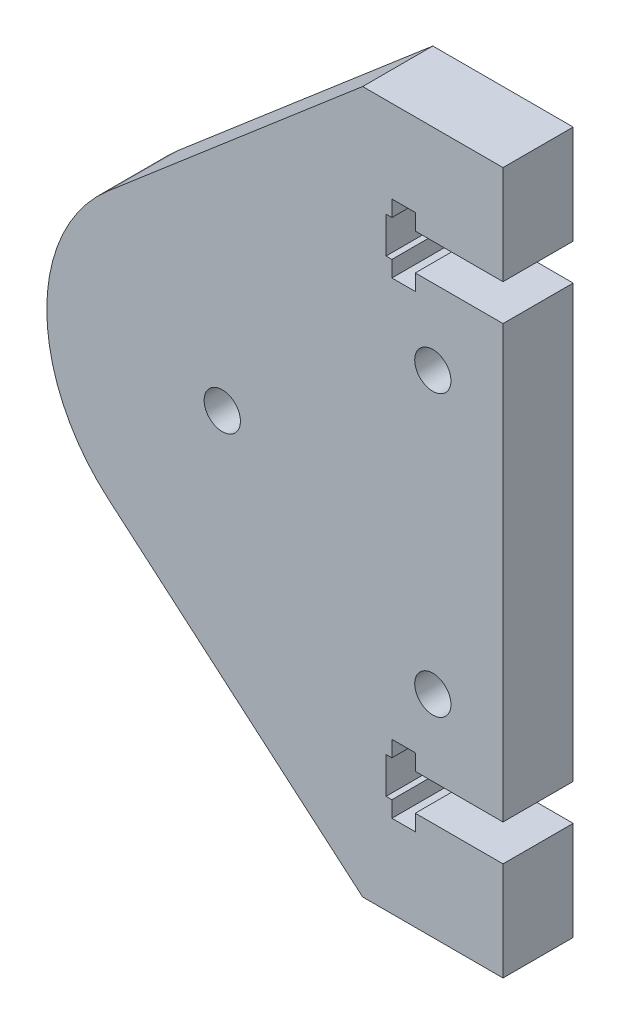
SolidWorks part; units mm, degrees
ref_plane "Płaszczyzna przednia" through (0, 0, 0) normal (0, 0, 1) x (1, 0, 0)
ref_plane "Płaszczyzna górna" through (0, 0, 0) normal (0, 1, 0) x (1, 0, 0)
ref_plane "Płaszczyzna prawa" through (0, 0, 0) normal (1, 0, 0) x (0, 0, -1)
sketch "Szkic1" plane through (0, 0, 0) normal (0, 0, 1) x (1, 0, 0)
  line L2 (-455.0646, -113.9558) -> (-476.8138, -95.3555)
  line L4 (-455.0646, -113.9558) -> (-443.0646, -113.9558)
  line L6 (-455.0646, -53.9558) -> (-476.8138, -72.5561)
  line L7 (-443.0646, -53.9558) -> (-455.0646, -53.9558)
  line L10 (-443.0646, -53.9558) -> (-443.0646, -113.9558)
  arc A0 (-476.8138, -72.5561) -> (-476.8138, -95.3555) centre (-467.0646, -83.9558) ccw
  dimension "D6" = 15
extrude "Dodanie-wyciągnięcie1" add sketch "Szkic1" along normal blind 6
sketch "Szkic2" plane through (0, 0, 6) normal (0, 0, 1) x (1, 0, 0)
  circle A0 centre (-467.0646, -83.9558) radius 1.55
  arc A1 (-476.8138, -72.5561) -> (-476.8138, -95.3555) centre (-467.0646, -83.9558) ccw construction
  dimension "D1" = 0
  dimension "D2" = 3.1
extrude "Wytnij-wyciągnięcie1" cut sketch "Szkic2" against normal blind 6
sketch "Szkic3" plane through (0, 0, 0) normal (0, 0, -1) x (-1, 0, 0)
  line L0 (443.0646, -113.9558) -> (443.0646, -53.9558) construction
  line L1 (443.0646, -105.5058) -> (450.5646, -105.5058)
  line L2 (443.0646, -105.5058) -> (443.0646, -102.4058)
  line L3 (443.0646, -102.4058) -> (450.5646, -102.4058)
  line L4 (453.0646, -105.5058) -> (453.0646, -102.4058)
  line L5 (452.5646, -105.5058) -> (453.0646, -105.5058)
  line L6 (452.5646, -106.8808) -> (450.5646, -106.8808)
  line L7 (452.5646, -106.8808) -> (452.5646, -105.5058)
  line L8 (452.5646, -101.0308) -> (450.5646, -101.0308)
  line L9 (450.5646, -106.8808) -> (450.5646, -105.5058)
  line L10 (450.5646, -102.4058) -> (450.5646, -101.0308)
  line L11 (452.5646, -102.4058) -> (453.0646, -102.4058)
  line L12 (452.5646, -102.4058) -> (452.5646, -101.0308)
  line L13 (455.0646, -113.9558) -> (443.0646, -113.9558) construction
  point P14 (443.0646, -103.9558)
  dimension "D1" = 10
  dimension "D2" = 0.5
  dimension "D3" = 2
  dimension "D4" = 3.1
  dimension "D5" = 1.375
  dimension "D6" = 5.85
  dimension "D7" = 10
extrude "Wytnij-wyciągnięcie2" cut sketch "Szkic3" against normal blind 6
pattern_linear "Szyk liniowy1" count 2 spacing 40 along (0, 1, 0) of "Wytnij-wyciągnięcie2"
sketch "Szkic4" plane through (0, 0, 0) normal (0, 0, -1) x (-1, 0, 0)
  circle A2 centre (449.0646, -95.9368) radius 1.55
  circle A3 centre (449.0646, -71.9708) radius 1.55
extrude "Wytnij-wyciągnięcie3" cut sketch "Szkic4" against normal blind 6
equation "\"tolerancja_wpusy\"=0.2"
equation "\"dlugosc_wpustu_duzy\"=20"
equation "\"srednica_otworu_M3\"=3.1"
equation "\"szerokosc_nogi_T\"=3.1"
equation "\"dlugosc_T_30\"=11"
equation "\"grubosc_na_nakretke_kwadrat\"=2"
equation "\"szerokosc_na_nakretke_kwadrat\"=5.85"
equation "\"wyokosc_nadstawki_T\"=0.5"
equation "\"dlugosc_T_20_6\"=14"
equation "\"D2@Szkic3\"=\"wyokosc_nadstawki_T\""
equation "\"D3@Szkic3\"=\"grubosc_na_nakretke_kwadrat\""
equation "\"D4@Szkic3\"=\"szerokosc_nogi_T\""
equation "\"D5@Szkic3\"=(\"szerokosc_na_nakretke_kwadrat\"-\"szerokosc_nogi_T\")/2"
equation "\"D6@Szkic3\"=\"szerokosc_na_nakretke_kwadrat\""
equation "\"D2@Szkic2\"=\"srednica_otworu_M3\""
